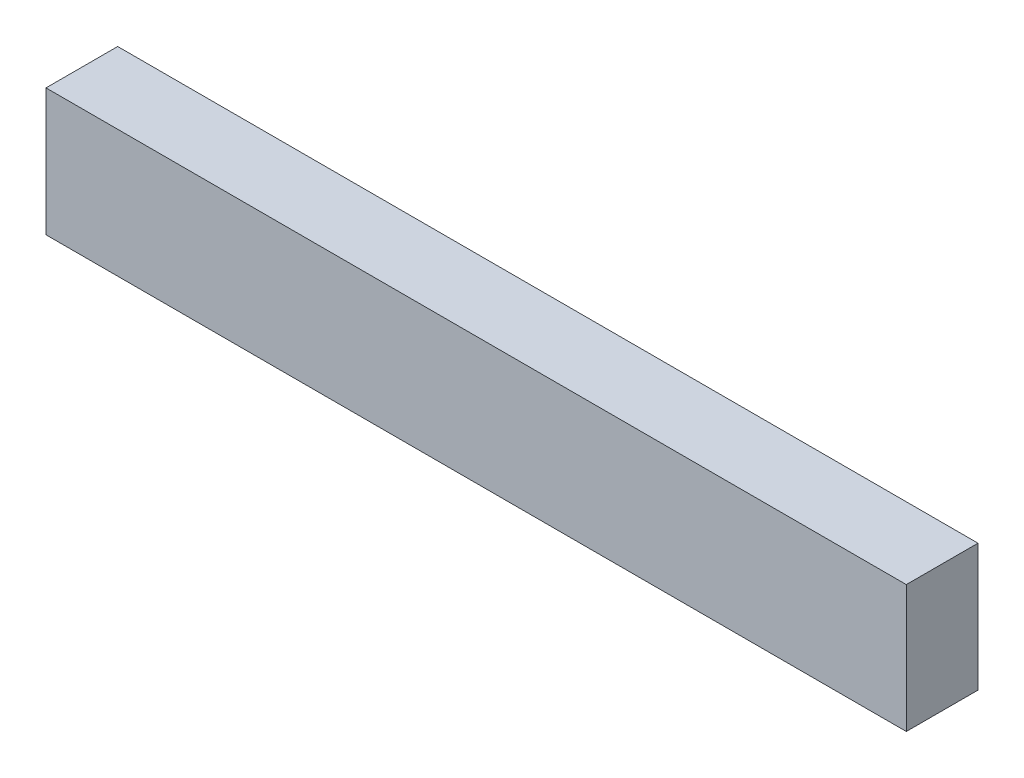
SolidWorks part; units mm, degrees
material "Custom Plastic"
ref_plane "X-Y Datum" through (0, 0, 0) normal (0, 0, 1) x (1, 0, 0)
ref_plane "X-Z Datum" through (0, 0, 0) normal (0, 1, 0) x (1, 0, 0)
ref_plane "Y-Z Datum" through (0, 0, 0) normal (1, 0, 0) x (0, 0, -1)
sketch "Sketch1" plane through (0, 0, 0) normal (0, 0, 1) x (1, 0, 0)
  line L1 (-24, 3.55) -> (24, 3.55)
  line L2 (-24, 3.55) -> (-24, -3.55)
  line L3 (-24, -3.55) -> (24, -3.55)
  line L4 (24, 3.55) -> (24, -3.55)
  line L5 (-24, 3.55) -> (24, -3.55) construction
  line L6 (-24, -3.55) -> (24, 3.55) construction
  point P0 (0, 0)
  dimension "D1" = 48
  dimension "D2" = 7.1
extrude "Boss-Extrude1" add sketch "Sketch1" along normal blind 4
